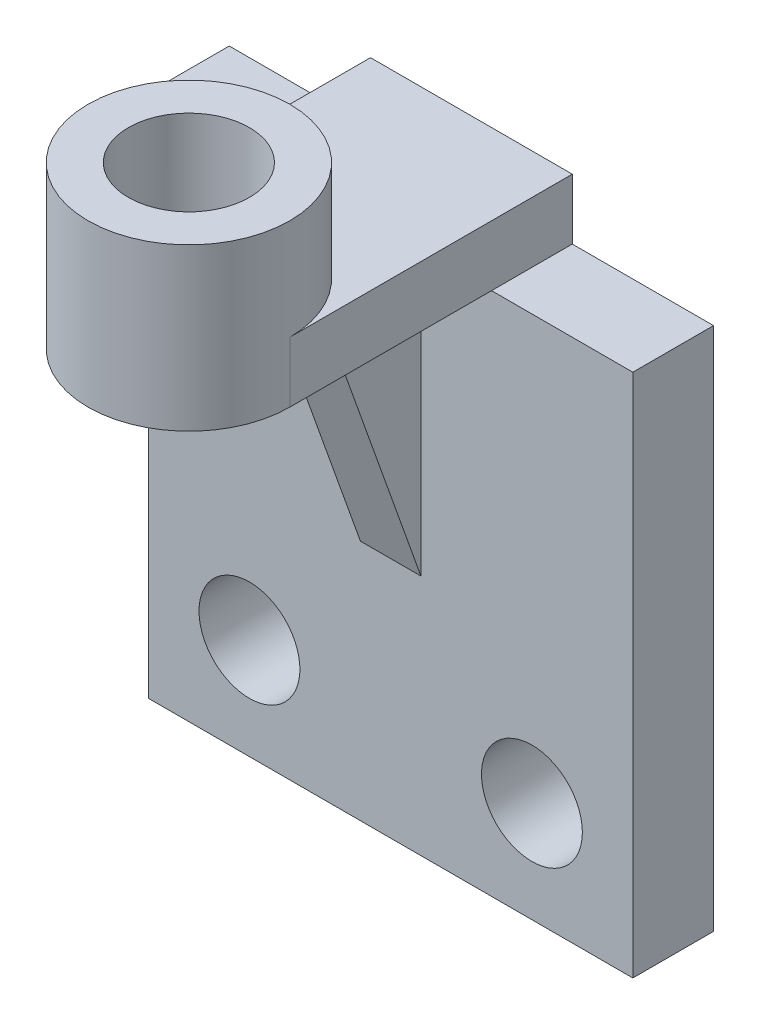
SolidWorks part; units mm, degrees
ref_plane "Спереди" through (0, 0, 0) normal (0, 0, 1) x (1, 0, 0)
ref_plane "Сверху" through (0, 0, 0) normal (0, 1, 0) x (1, 0, 0)
ref_plane "Справа" through (0, 0, 0) normal (1, 0, 0) x (0, 0, -1)
sketch "Эскиз1" plane through (0, 0, 0) normal (0, 0, 1) x (1, 0, 0)
  line L1 (-60, -65) -> (60, -65)
  line L2 (-60, -65) -> (-60, 65)
  line L3 (-60, 65) -> (60, 65)
  line L4 (60, -65) -> (60, 65)
  line L5 (-60, -65) -> (60, 65) construction
  line L6 (-60, 65) -> (60, -65) construction
  point P0 (0, 0)
  dimension "D1" = 120
  dimension "D2" = 130
extrude "Бобышка-Вытянуть1" add sketch "Эскиз1" along normal blind 20
sketch "Эскиз2" plane through (0, 0, 20) normal (0, 0, 1) x (1, 0, 0)
  line L0 (-60, -65) -> (60, -65) construction
  line L1 (60, -65) -> (60, 65) construction
  circle A0 centre (35, -40) radius 12.5
  dimension "D1" = 25
  dimension "D2" = 25
  dimension "D3" = 25
extrude "Вырез-Вытянуть1" cut sketch "Эскиз2" against normal through all
mirror "Зеркальное отражение1" about plane through (0, 0, 0) normal (1, 0, 0) of "Вырез-Вытянуть1"
sketch "Эскиз3" plane through (0, 65, 0) normal (0, 1, 0) x (1, 0, 0)
  line L0 (60, 0) -> (-60, 0) construction
  line L1 (-25, -70) -> (25, -70)
  line L2 (-25, -70) -> (-25, 0)
  line L3 (-25, 0) -> (25, 0)
  line L4 (25, -70) -> (25, 0)
  line L5 (-25, -70) -> (25, 0) construction
  line L6 (-25, 0) -> (25, -70) construction
  point P0 (0, -35)
  dimension "D1" = 70
  dimension "D2" = 50
extrude "Бобышка-Вытянуть2" add sketch "Эскиз3" along normal blind 15
sketch "Эскиз4" plane through (0, 80, 0) normal (0, 1, 0) x (1, 0, 0)
  line L0 (-25, -70) -> (25, -70) construction
  circle A0 centre (0, -70) radius 25
extrude "Бобышка-Вытянуть3" add sketch "Эскиз4" along normal blind 25 and the other way up to surface other way up to face at (0, 65, 45)
sketch "Эскиз5" plane through (0, 105, 0) normal (0, 1, 0) x (1, 0, 0)
  circle A0 centre (0, -70) radius 15
  dimension "D1" = 30
extrude "Вырез-Вытянуть2" cut sketch "Эскиз5" against normal through all
sketch "Эскиз6" plane through (0, 0, 0) normal (1, 0, 0) x (0, 0, -1)
  line L0 (-45, 65) -> (-20, -5)
  line L1 (-70, 65) -> (-20, 65) construction
  line L2 (-20, -65) -> (-20, 65) construction
  dimension "D1" = 70
rib "Ребро1" sketch "Эскиз6" sketch "Эскиз6" thickness 15 extrusion direction parallel to sketch draft on no parameters "D1"=15
